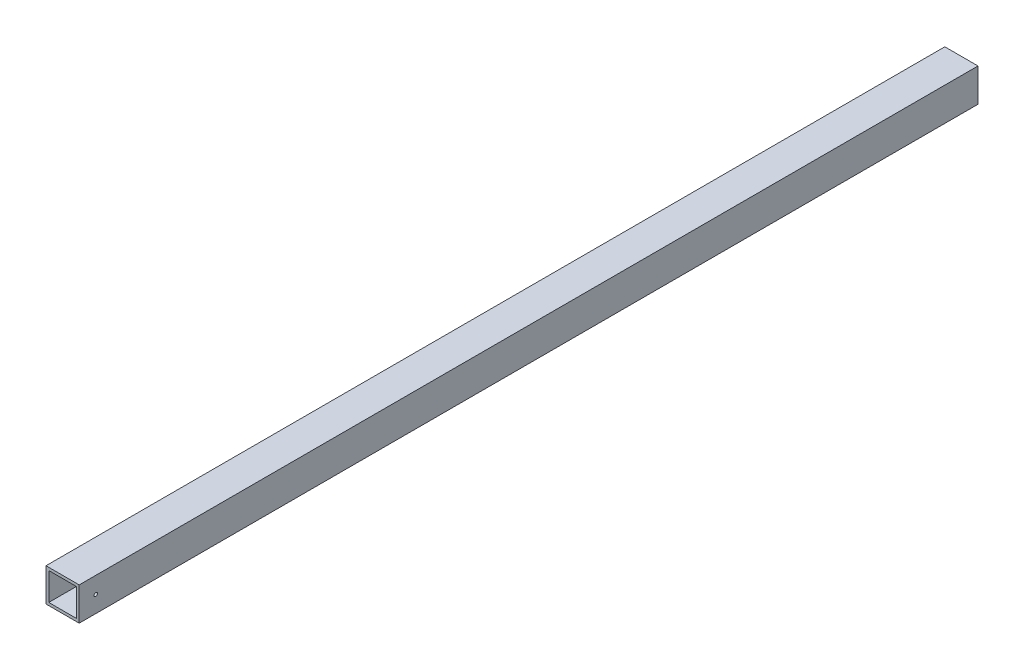
SolidWorks part; units mm, degrees
ref_plane "前视基准面" through (0, 0, 0) normal (0, 0, 1) x (1, 0, 0)
ref_plane "上视基准面" through (0, 0, 0) normal (0, 1, 0) x (1, 0, 0)
ref_plane "右视基准面" through (0, 0, 0) normal (1, 0, 0) x (0, 0, -1)
sketch "草图1" plane through (0, 0, 0) normal (0, 0, 1) x (1, 0, 0)
  line L0 (-12, 12) -> (12, 12)
  line L1 (-10, 10) -> (10, 10)
  line L2 (-10, 10) -> (-10, -10)
  line L3 (-10, -10) -> (10, -10)
  line L4 (10, 10) -> (10, -10)
  line L5 (-10, 10) -> (10, -10) construction
  line L6 (-10, -10) -> (10, 10) construction
  line L7 (12, 12) -> (12, -12)
  line L8 (-12, -12) -> (12, -12)
  line L9 (-12, 12) -> (-12, -12)
  point P0 (0, 0)
  dimension "D1" = 20
  dimension "D2" = 20
  dimension "D3" = 2
extrude "凸台-拉伸1" add sketch "草图1" along normal blind 650
sketch "草图4" plane through (-12, 0, 0) normal (-1, 0, 0) x (0, 0, 1)
  line L0 (650, 12) -> (650, -12) construction
  circle A0 centre (638, 0) radius 2 construction
  dimension "D1" = 12
hole_wizard "M3 螺纹孔的螺纹孔钻头2" positions "3D草图2" profile "草图5" hole size "M3" standard "GB" end condition through all
sketch3d "3D草图2"
  point P0 (-12, 0, 638)
sketch "草图5" plane through (-12, 0, 638) normal (0, 1, 0) x (0, 0, 1)
  line L0 (0, 0) -> (0, 24)
  line L1 (0, 24) -> (1.25, 24)
  line L2 (1.25, 24) -> (1.25, 0)
  line L5 (1.25, 0) -> (0, 0)
  line L11 (0, -6.35) -> (0, 107.95) construction
  dimension "通孔孔直径" = 2.5
  dimension "通孔孔深度" = 24
